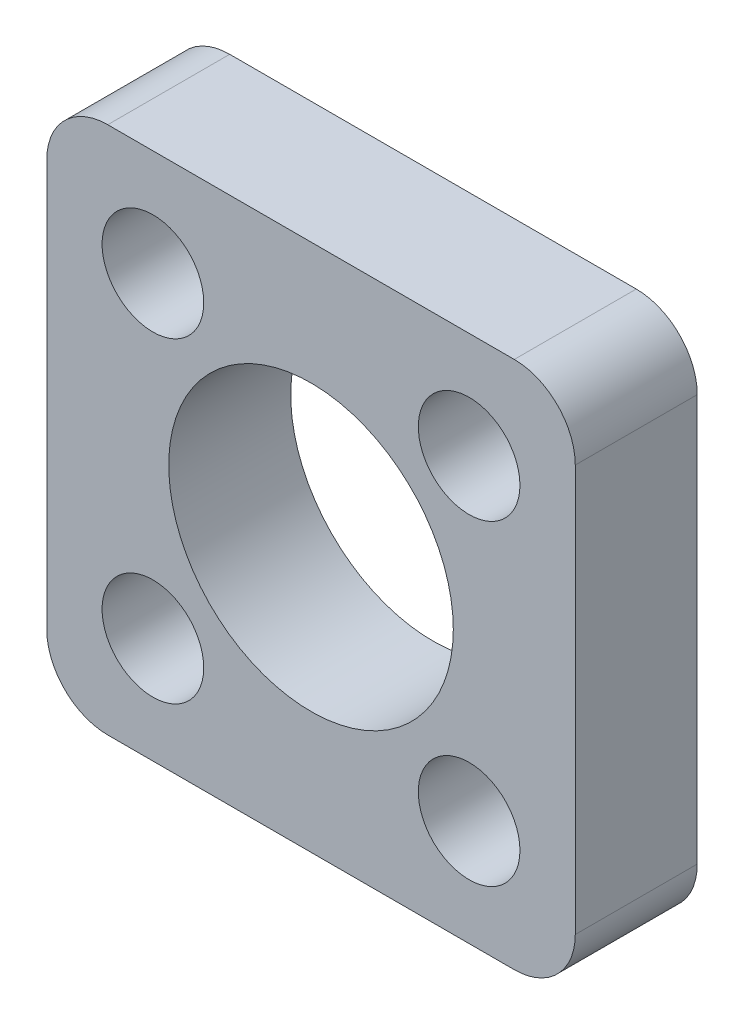
SolidWorks part; units mm, degrees
ref_plane "Front Plane" through (0, 0, 0) normal (0, 0, 1) x (1, 0, 0)
ref_plane "Top Plane" through (0, 0, 0) normal (0, 1, 0) x (1, 0, 0)
ref_plane "Right Plane" through (0, 0, 0) normal (1, 0, 0) x (0, 0, -1)
sketch "Sketch1" plane through (0, 0, 0) normal (0, 0, 1) x (1, 0, 0)
  line L0 (-3.8891, 3.8891) -> (0, 0) construction
  line L1 (5, -6.5) -> (-5, -6.5)
  line L2 (6.5, -5) -> (6.5, 5)
  line L3 (5, 6.5) -> (-5, 6.5)
  line L4 (-6.5, -5) -> (-6.5, 5)
  line L5 (6.5, -6.5) -> (-6.5, 6.5) construction
  line L6 (6.5, 6.5) -> (-6.5, -6.5) construction
  line L7 (0, 0) -> (0, 6.5) construction
  arc A0 (-5, 6.5) -> (-6.5, 5) centre (-5, 5) ccw
  arc A1 (6.5, 5) -> (5, 6.5) centre (5, 5) ccw
  arc A2 (5, -6.5) -> (6.5, -5) centre (5, -5) ccw
  arc A3 (-5, -6.5) -> (-6.5, -5) centre (-5, -5) cw
  circle A4 centre (0, 0) radius 5.5 construction
  circle A5 centre (0, 0) radius 3.5
  circle A6 centre (-3.8891, 3.8891) radius 1.25
  circle A7 centre (3.8891, 3.8891) radius 1.25
  circle A8 centre (3.8891, -3.8891) radius 1.25
  circle A9 centre (-3.8891, -3.8891) radius 1.25
  point P0 (0, 0)
  point P33 (0, 0)
  dimension "D3" = 1.5
  dimension "D4" = 11
  dimension "D5" = 2.5
  dimension "D7" = 7
  dimension "D1" = 13
  dimension "D2" = 13
  dimension "D6" = 45
  dimension "D8" = 4
extrude "Boss-Extrude1" add sketch "Sketch1" along normal blind 3
